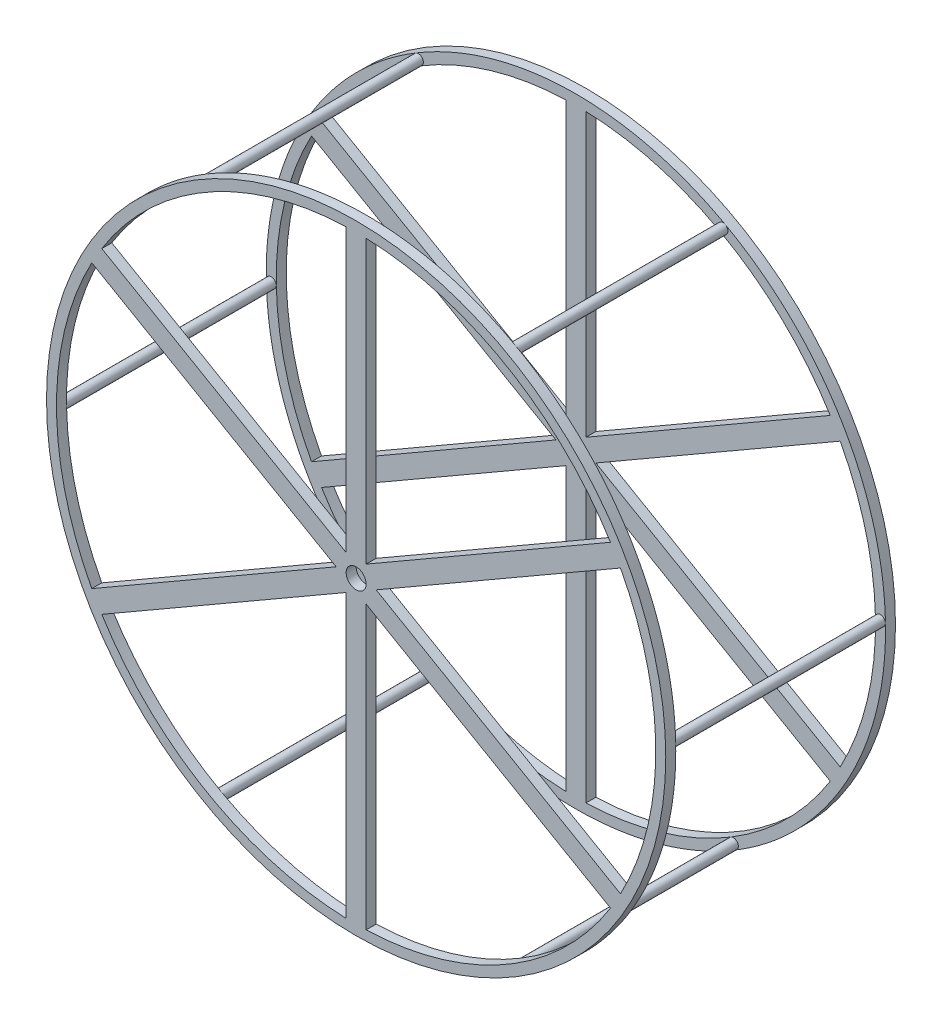
SolidWorks part; units mm, degrees
ref_plane "Front Plane" through (0, 0, 0) normal (0, 0, 1) x (1, 0, 0)
ref_plane "Top Plane" through (0, 0, 0) normal (0, 1, 0) x (1, 0, 0)
ref_plane "Right Plane" through (0, 0, 0) normal (1, 0, 0) x (0, 0, -1)
sketch "Sketch1" plane through (0, 0, 0) normal (0, 0, 1) x (1, 0, 0)
  circle A0 centre (0, 0) radius 150
  circle A1 centre (0, 0) radius 155
  dimension "D1" = 300
  dimension "D2" = 5
extrude "Boss-Extrude1" add sketch "Sketch1" along normal blind 115
sketch "Sketch4" plane through (0, 0, 0) normal (0, 0, -1) x (-1, 0, 0)
  line L0 (0, 150) -> (0, -150) construction
  line L1 (-5, 150) -> (-5, -150)
  line L2 (5, 150) -> (5, -150)
  line L3 (-5, 150) -> (5, 150)
  line L4 (-5, -150) -> (5, -150)
  circle A0 centre (0, 0) radius 150 construction
  dimension "D1" = 5
  dimension "D2" = 5
extrude "Boss-Extrude3" add sketch "Sketch4" against normal blind 115
pattern_circular "CirPattern1" count 3 every 60 about axis through (0, 0, 0) along (0, 0, 1) of "Boss-Extrude3"
sketch "Sketch2" plane through (0, 0, 0) normal (1, 0, 0) x (0, 0, -1)
  line L0 (0, 155) -> (-115, 155) construction
  line L1 (-5, -155) -> (-110, -155)
  line L2 (-5, -155) -> (-5, 155)
  line L3 (-5, 155) -> (-110, 155)
  line L4 (-110, -155) -> (-110, 155)
  line L5 (-5, -155) -> (-110, 155) construction
  line L6 (-5, 155) -> (-110, -155) construction
  line L7 (-115, 155) -> (-115, -155) construction
  line L8 (0, -155) -> (0, 155) construction
  line L9 (-115, -155) -> (0, -155) construction
  point P0 (-57.5, 0)
  dimension "D1" = 5
  dimension "D2" = 5
extrude "Cut-Extrude1" cut sketch "Sketch2" against normal through all both and the other way through all
sketch "Sketch3" plane through (0, 0, 110) normal (0, 0, -1) x (-1, 0, 0)
  line L0 (0, -1000) -> (0, 49000) construction
  line L1 (77.5958, 128.3701) -> (80.0963, 132.7011) construction
  arc A0 (127.3316, 79.2884) -> (5, 149.9166) centre (0, 0) ccw construction
  circle A1 centre (0, 0) radius 155 construction
  circle A2 centre (78.8461, 130.5356) radius 2.5
  dimension "D1" = 30
extrude "Boss-Extrude2" add sketch "Sketch3" along normal up to surface (105 mm away) up to face at (48.7219, 84.3889, 5)
pattern_circular "CirPattern2" count 6 over 360 about axis through (0, 0, 0) along (0, 0, 1) of "Boss-Extrude2"
sketch "Sketch5" plane through (0, 0, 0) normal (0, 0, -1) x (-1, 0, 0)
  circle A0 centre (0, 0) radius 5
  dimension "D1" = 10
extrude "Cut-Extrude2" cut sketch "Sketch5" against normal through all both and the other way through all
ref_plane "Plane1" through (0, 0, 2.5) normal (0, 0, -1) x (-1, 0, 0)
sketch "Sketch6" plane through (0, 0, 2.5) normal (0, 0, -1) x (-1, 0, 0)
  circle A0 centre (0, 0) radius 155 construction
  circle A1 centre (0, 0) radius 155
